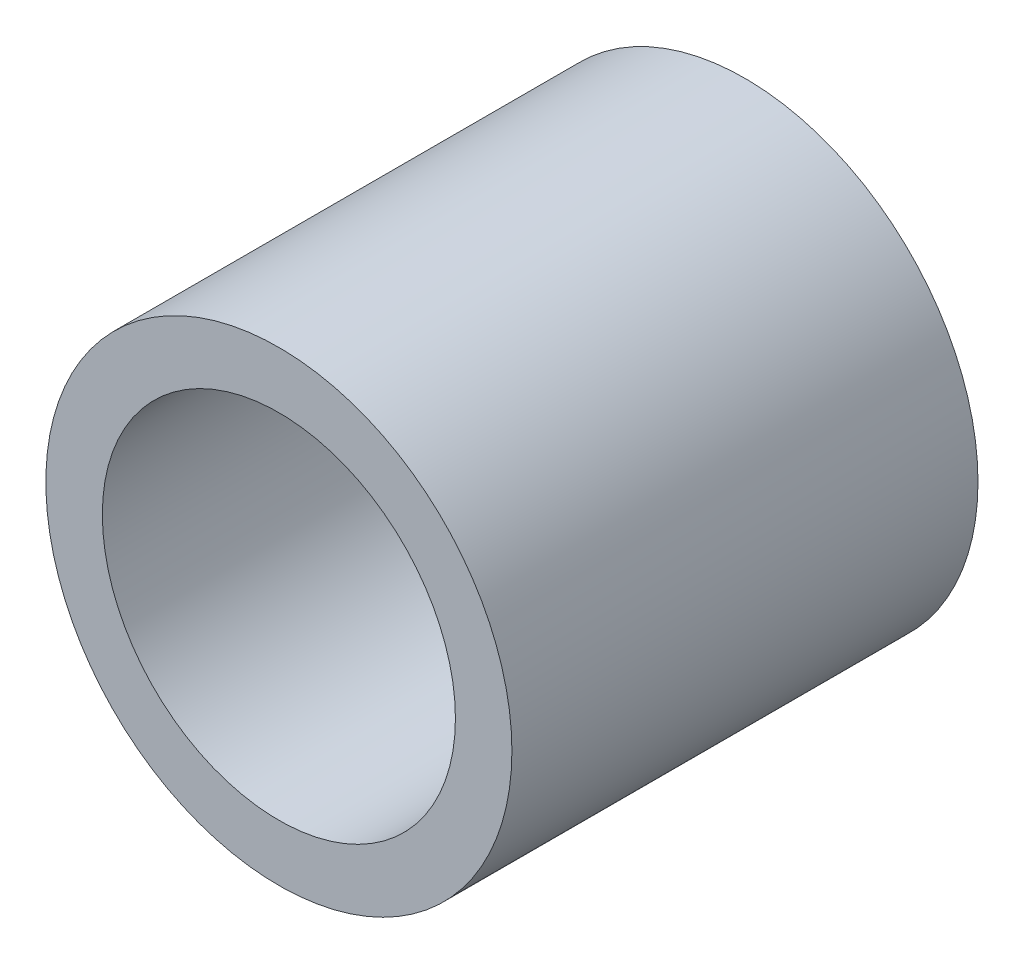
SolidWorks part; units mm, degrees
ref_plane "Plano frontal" through (0, 0, 0) normal (0, 0, 1) x (1, 0, 0)
ref_plane "Plano superior" through (0, 0, 0) normal (0, 1, 0) x (1, 0, 0)
ref_plane "Plano direito" through (0, 0, 0) normal (1, 0, 0) x (0, 0, -1)
sketch "Esboço1" plane through (0, 0, 0) normal (0, 0, 1) x (1, 0, 0)
  circle A0 centre (0, 0) radius 6.25
  circle A1 centre (0, 0) radius 8.25
  dimension "D1" = 12.5
  dimension "D2" = 16.5
extrude "Ressalto-extrusão1" add sketch "Esboço1" along normal blind 16.5
